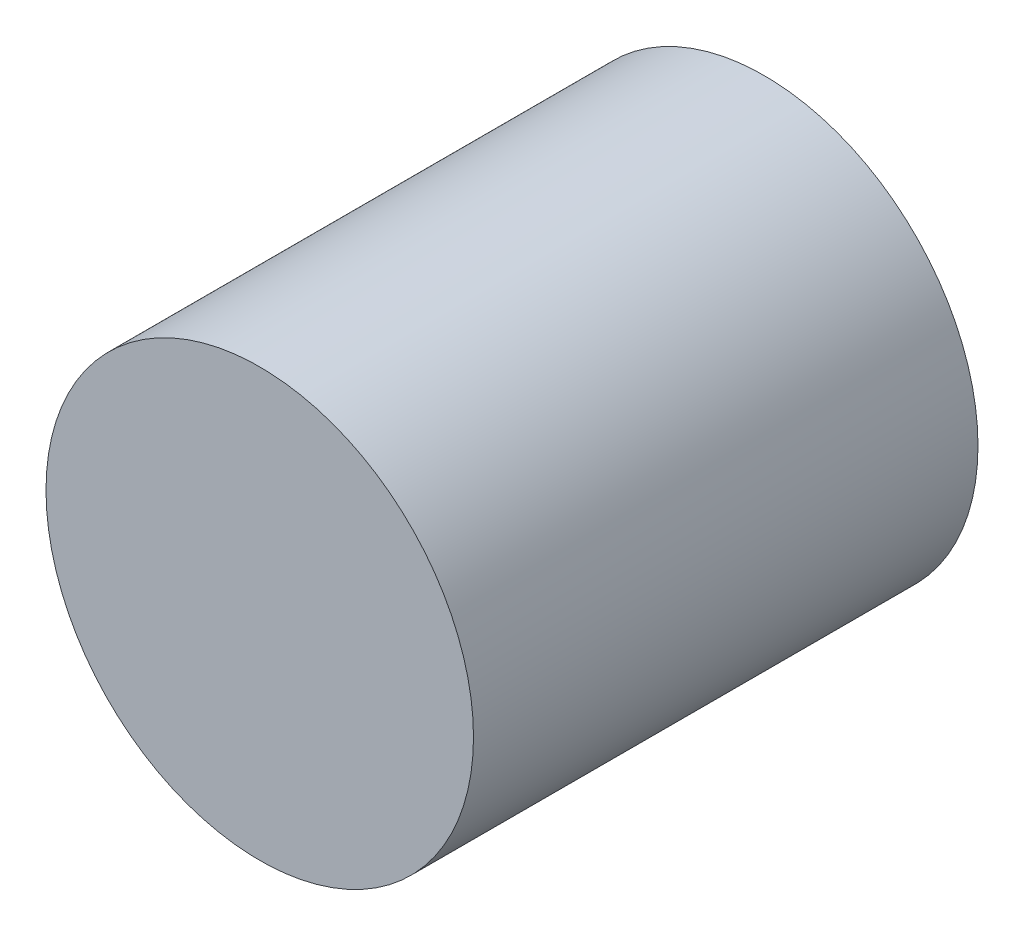
SolidWorks part; units mm, degrees
ref_plane "Plan de face" through (0, 0, 0) normal (0, 0, 1) x (1, 0, 0)
ref_plane "Plan de dessus" through (0, 0, 0) normal (0, 1, 0) x (1, 0, 0)
ref_plane "Plan de droite" through (0, 0, 0) normal (1, 0, 0) x (0, 0, -1)
sketch "Esquisse1" plane through (0, 0, 0) normal (0, 0, 1) x (1, 0, 0)
  circle A0 centre (0, 0) radius 16.1
extrude "Boss.-Extru.1" add sketch "Esquisse1" along normal blind 38
